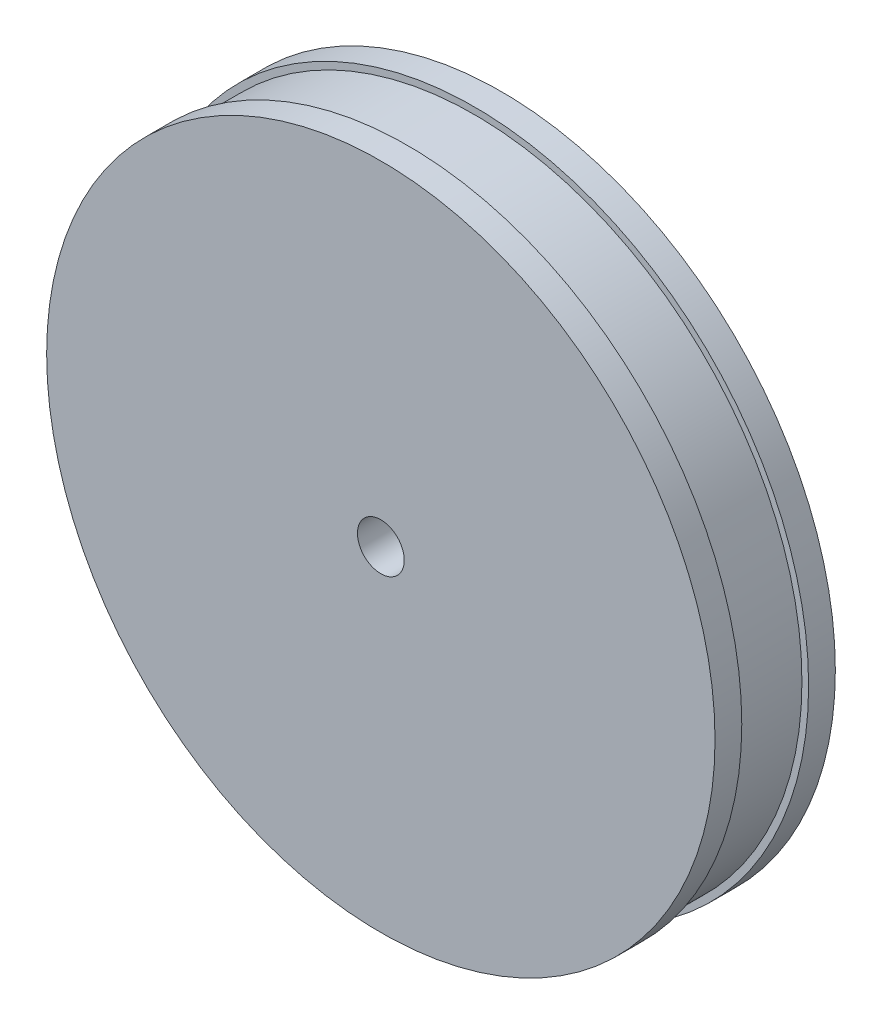
SolidWorks part; units mm, degrees
ref_plane "Plan de face" through (0, 0, 0) normal (0, 0, 1) x (1, 0, 0)
ref_plane "Plan de dessus" through (0, 0, 0) normal (0, 1, 0) x (1, 0, 0)
ref_plane "Plan de droite" through (0, 0, 0) normal (1, 0, 0) x (0, 0, -1)
sketch "Esquisse1" plane through (0, 0, 0) normal (0, 0, 1) x (1, 0, 0)
  circle A0 centre (0, 0) radius 25
  circle A1 centre (0, 0) radius 24.5
  dimension "D1" = 50
  dimension "D2" = 49
extrude "Boss.-Extru.1" add sketch "Esquisse1" along normal blind 5 contours A1
sketch "Esquisse2" plane through (0, 0, 0) normal (0, 0, -1) x (-1, 0, 0)
  circle A0 centre (0, 0) radius 25
  dimension "D1" = 50
extrude "Boss.-Extru.2" add sketch "Esquisse2" along normal blind 2
sketch "Esquisse3" plane through (0, 0, 5) normal (0, 0, 1) x (1, 0, 0)
  circle A0 centre (0, 0.5386) radius 25
  dimension "D1" = 50
extrude "Boss.-Extru.3" [suppressed] add sketch "Esquisse3" along normal blind 2
sketch "Esquisse4" plane through (0, 0, -2) normal (0, 0, -1) x (-1, 0, 0)
  line L0 (1.3175, 1.1518) -> (-1.3175, 1.1518)
  circle A0 centre (0, 0) radius 1.75
  dimension "D1" = 3.5
sketch "Esquisse5" plane through (0, 0, 5) normal (0, 0, 1) x (1, 0, 0)
  circle A0 centre (0, 0) radius 25
  dimension "D1" = 50
extrude "Boss.-Extru.4" add sketch "Esquisse5" along normal blind 2
extrude "Enlèv. mat.-Extru.1" cut sketch "Esquisse4" against normal through all contours A0
